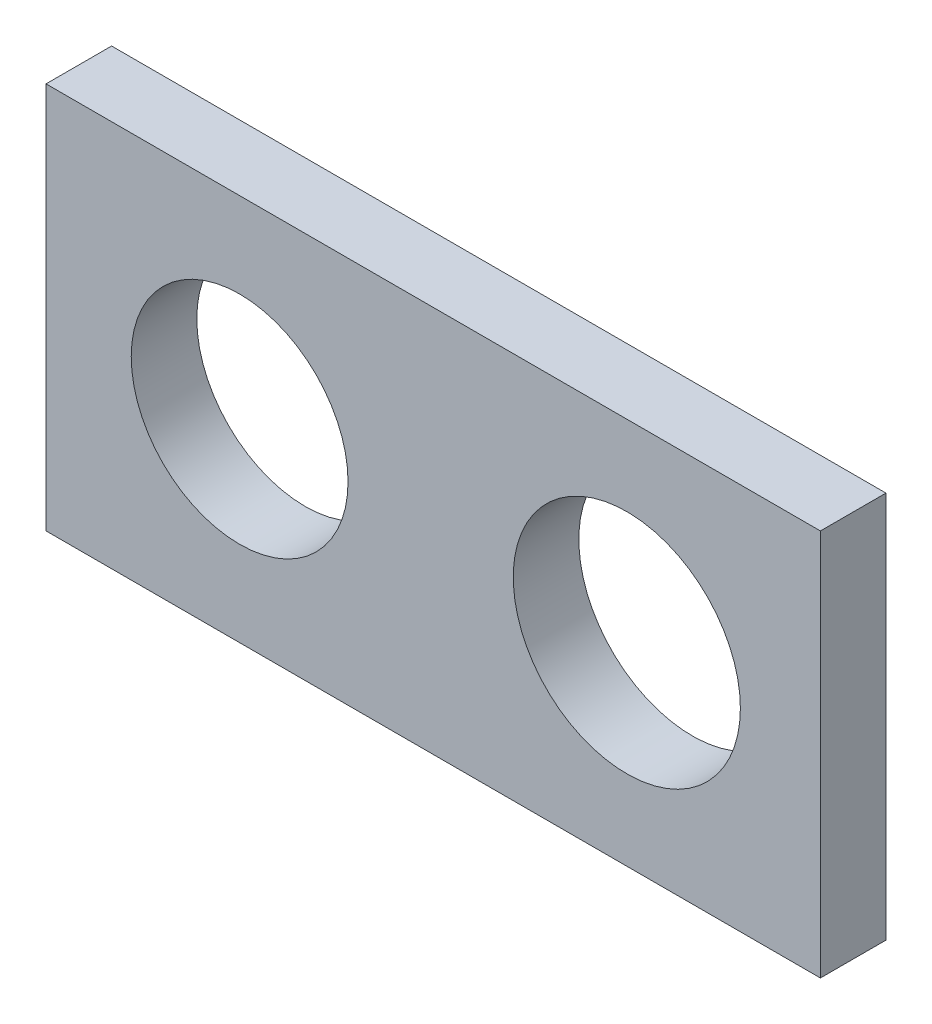
SolidWorks part; units mm, degrees
ref_plane "Front Plane" through (0, 0, 0) normal (0, 0, 1) x (1, 0, 0)
ref_plane "Top Plane" through (0, 0, 0) normal (0, 1, 0) x (1, 0, 0)
ref_plane "Right Plane" through (0, 0, 0) normal (1, 0, 0) x (0, 0, -1)
sketch "Sketch1" plane through (0, 0, 0) normal (0, 0, 1) x (1, 0, 0)
  line L1 (-15, -7.5) -> (15, -7.5)
  line L2 (-15, -7.5) -> (-15, 7.5)
  line L3 (-15, 7.5) -> (15, 7.5)
  line L4 (15, -7.5) -> (15, 7.5)
  line L5 (-15, -7.5) -> (15, 7.5) construction
  line L6 (-15, 7.5) -> (15, -7.5) construction
  line L7 (-15, 0) -> (15, 0) construction
  line L10 (-7.5, 0) -> (-7.5, 7.5) construction
  line L11 (0, 0) -> (15, 0) construction
  line L12 (7.5, 0) -> (7.5, 7.5) construction
  circle A1 centre (-7.5, 0) radius 4.2
  circle A2 centre (7.5, 0) radius 4.4
  point P0 (0, 0)
  dimension "D3" = 8.4
  dimension "D4" = 8.8
  dimension "D1" = 30
  dimension "D2" = 15
extrude "Boss-Extrude1" add sketch "Sketch1" along normal blind 2.54
